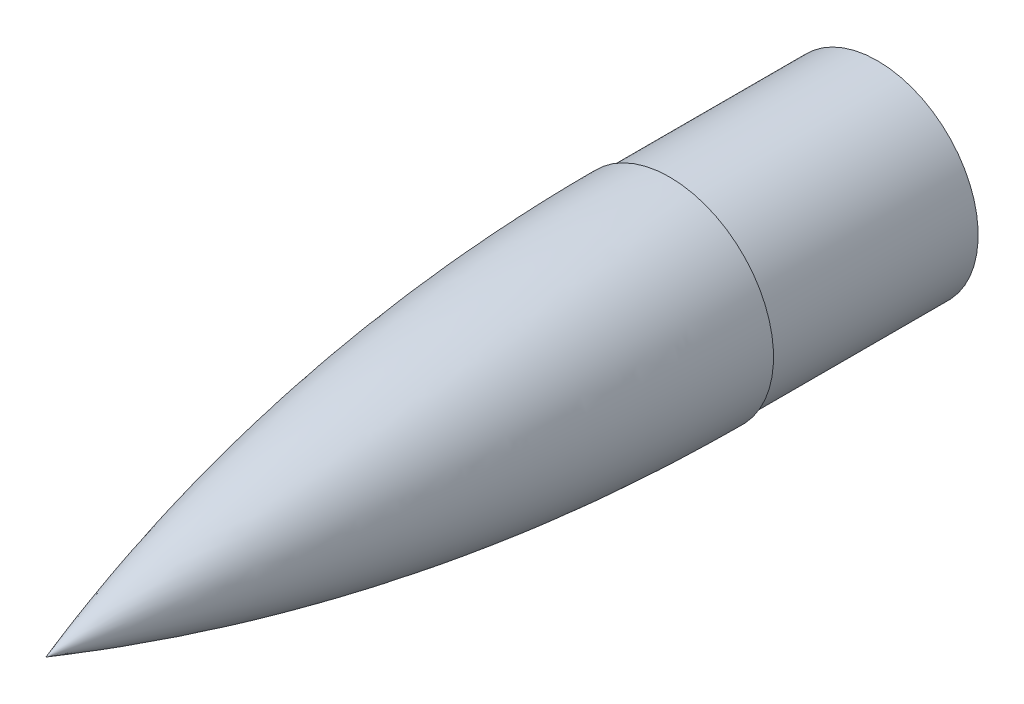
SolidWorks part; units mm, degrees
ref_plane "Front Plane" through (0, 0, 0) normal (0, 0, 1) x (1, 0, 0)
ref_plane "Top Plane" through (0, 0, 0) normal (0, 1, 0) x (1, 0, 0)
ref_plane "Right Plane" through (0, 0, 0) normal (1, 0, 0) x (0, 0, -1)
sketch "Sketch1" plane through (0, 0, 0) normal (1, 0, 0) x (0, 0, -1)
  line L0 (0, 0) -> (-304.8, 0)
  line L1 (0, 50.8) -> (0, 0)
  spline S0 degree 4 poles (-333.7559, -10.4609) (-333.1491, -10.2303) (-331.935, -9.7704) (-330.1111, -9.0833) (-327.6807, -8.1752) (-325.2521, -7.2757) (-322.8443, -6.3911) (-320.4222, -5.5092) (-318.0523, -4.6528) (-315.5967, -3.7743) (-313.2988, -2.9572) (-310.6898, -2.0407) (-308.6784, -1.3364) (-305.6446, -0.2893) (-304.2644, 0.1843) (-301.7409, 1.0442) (-299.7883, 1.7036) (-297.7989, 2.3706) (-295.7822, 3.042) (-293.7777, 3.7041) (-291.7681, 4.3629) (-289.7465, 5.0206) (-287.7123, 5.6774) (-268.6886, 11.7712) (-231.3216, 22.614) (-177.0619, 35.2039) (-118.245, 44.0822) (-74.1164, 48.1343) (-47.1478, 49.6547) (-36.3533, 50.114) (-28.7946, 50.366) (-23.9345, 50.4982) (-20.6942, 50.5739) (-17.7411, 50.6339) (-15.6039, 50.6716) (-13.478, 50.7043) (-11.364, 50.732) (-9.5169, 50.7528) (-7.3919, 50.7719) (-5.292, 50.7861) (-3.2349, 50.7956) (-0.5722, 50.8006) (0.8792, 50.8003) (4.0577, 50.7938) (6.1747, 50.7802) (8.9066, 50.7599) (11.3251, 50.7327) (13.9044, 50.6988) (16.4005, 50.6581) (18.9513, 50.6104) (21.4913, 50.5556) (24.0547, 50.4936) (26.6233, 50.4243) (28.5524, 50.367) (29.8374, 50.3265) (30.4799, 50.3056) knots 0 0 0 0 0 0.006987 0.013974 0.020962 0.027949 0.03481 0.04167 0.048531 0.055392 0.062253 0.069114 0.075975 0.082836 0.088524 0.094212 0.099901 0.105589 0.111278 0.116966 0.122654 0.128343 0.134156 0.13997 0.33763 0.546917 0.73295 0.779458 0.814339 0.837593 0.84922 0.860847 0.866661 0.872474 0.881007 0.883851 0.88954 0.895228 0.900916 0.906605 0.912293 0.917981 0.924774 0.931567 0.938359 0.945152 0.951945 0.958738 0.96553 0.972323 0.979242 0.986161 0.993081 1 1 1 1 1 construction
  spline S1 degree 4 poles (-304.8, 0) (-304.3824, 0.1432) (-303.5408, 0.4309) (-301.7409, 1.0442) (-299.7883, 1.7036) (-297.7989, 2.3706) (-295.7822, 3.042) (-293.7777, 3.7041) (-291.7681, 4.3629) (-289.7465, 5.0206) (-287.7123, 5.6774) (-268.6886, 11.7712) (-231.3216, 22.614) (-177.0619, 35.2039) (-118.245, 44.0822) (-74.1164, 48.1343) (-47.1478, 49.6547) (-36.3533, 50.114) (-28.7946, 50.366) (-23.9345, 50.4982) (-20.6942, 50.5739) (-17.7411, 50.6339) (-15.6039, 50.6716) (-13.478, 50.7043) (-11.364, 50.732) (-9.5169, 50.7528) (-7.3919, 50.7719) (-5.292, 50.7861) (-3.2349, 50.7956) (-1.3303, 50.7992) (-0.4414, 50.8) (0, 50.8) knots 0.082836 0.082836 0.082836 0.082836 0.082836 0.088524 0.094212 0.099901 0.105589 0.111278 0.116966 0.122654 0.128343 0.134156 0.13997 0.33763 0.546917 0.73295 0.779458 0.814339 0.837593 0.84922 0.860847 0.866661 0.872474 0.881007 0.883851 0.88954 0.895228 0.900916 0.906605 0.912293 0.917981 0.917981 0.917981 0.917981 0.917981
  dimension "D1" = 304.8
revolve "Revolve1" add sketch "Sketch1" angle 360 about L0
sketch "Sketch2" plane through (0, 0, 0) normal (0, 0, -1) x (-1, 0, 0)
  circle A0 centre (0, 0) radius 49.2125
  dimension "D5" = 98.425
extrude "Boss-Extrude1" add sketch "Sketch2" along normal blind 50.8
sketch "Sketch3" plane through (0, 0, -50.8) normal (0, 0, -1) x (-1, 0, 0)
  line L0 (0, 0) -> (0, 43.6577) construction
  circle A0 centre (-25.4, 0) radius 9.525
  dimension "D1" = 19.05
  dimension "D2" = 25.4
revolve "Cut-Revolve3" cut sketch "Sketch3" angle 360 about L0
sketch "Sketch4" plane through (0, 0, -50.8) normal (0, 0, -1) x (-1, 0, 0)
  line L0 (0, 0) -> (0, 38.554) construction
  circle A0 centre (-25.4, 0) radius 9.525
  circle A2 centre (0, 0) radius 49.2125
  circle A3 centre (25.4, 0) radius 9.525
  circle A4 centre (0, 0) radius 49.2125 construction
  dimension "D1" = 19.05
  dimension "D2" = 25.4
extrude "Boss-Extrude2" add sketch "Sketch4" along normal blind 50.8
sketch "Sketch5" plane through (0, 0, 0) normal (0, 1, 0) x (1, 0, 0)
  line L0 (0, 0) -> (0, -304.8) construction
